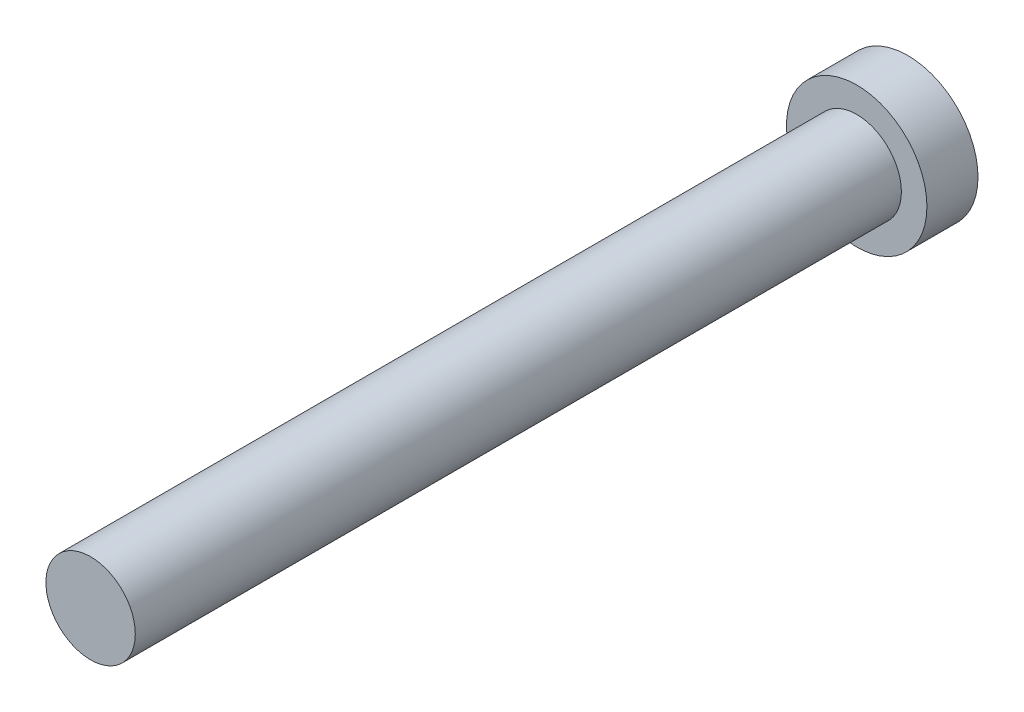
SolidWorks part; units mm, degrees
ref_plane "前基準面" through (0, 0, 0) normal (0, 0, 1) x (1, 0, 0)
ref_plane "上基準面" through (0, 0, 0) normal (0, 1, 0) x (1, 0, 0)
ref_plane "右基準面" through (0, 0, 0) normal (1, 0, 0) x (0, 0, -1)
sketch "草圖1" plane through (0, 0, 0) normal (0, 0, 1) x (1, 0, 0)
  circle A0 centre (0, 0) radius 2.75
  dimension "D1" = 5.5
extrude "伸長1" add sketch "草圖1" along normal blind 2
sketch "草圖2" plane through (0, 0, 2) normal (0, 0, 1) x (1, 0, 0)
  circle A0 centre (0, 0) radius 1.75
  dimension "D1" = 3.5
extrude "伸長2" add sketch "草圖2" along normal blind 30
